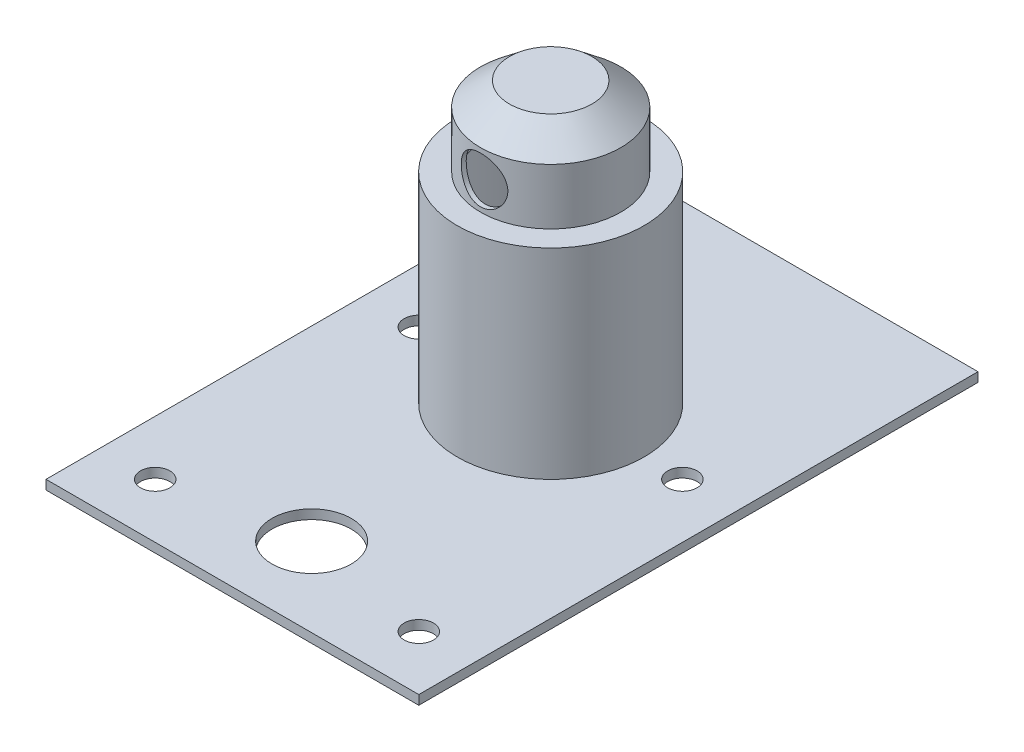
SolidWorks part; units mm, degrees
ref_plane "Front Plane" through (0, 0, 0) normal (0, 0, 1) x (1, 0, 0)
ref_plane "Top Plane" through (0, 0, 0) normal (0, 1, 0) x (1, 0, 0)
ref_plane "Right Plane" through (0, 0, 0) normal (1, 0, 0) x (0, 0, -1)
sketch "Sketch1" plane through (0, 0, 0) normal (0, 1, 0) x (1, 0, 0)
  line L0 (-35.5915, 84.198) -> (44.4085, 4.198) construction
  line L1 (-35.5915, 84.198) -> (44.4085, 84.198) construction
  line L2 (-35.5915, 84.198) -> (-35.5915, 4.198)
  line L3 (-35.5915, 4.198) -> (44.4085, 4.198)
  line L4 (44.4085, 84.198) -> (44.4085, 4.198)
  line L5 (-35.5915, 4.198) -> (44.4085, 84.198) construction
  line L6 (4.4085, 44.198) -> (106.3368, 44.198) construction
  line L7 (-35.5915, 84.198) -> (-35.5915, 124.198)
  line L8 (-35.5915, 124.198) -> (44.4085, 124.198)
  line L9 (44.4085, 124.198) -> (44.4085, 84.198)
  circle A0 centre (-23.8758, 72.4822) radius 3.15
  circle A4 centre (4.4085, 21.198) radius 8.5
  circle A8 centre (32.6928, 72.4822) radius 3.15
  circle A9 centre (-23.8758, 15.9137) radius 3.15
  circle A10 centre (32.6928, 15.9137) radius 3.15
  point P9 (4.4085, 44.198)
  point P15 (4.4085, 44.198)
  dimension "D1" = 6.3
  dimension "D4" = 23
  dimension "D5" = 17
  dimension "D2" = 40
  dimension "D6" = 80
  dimension "D3" = 120
extrude "Boss-Extrude1" add sketch "Sketch1" along normal blind 2
ref_plane "Plane1" through (0, 0, -72.5) normal (0, 0, 1) x (1, 0, 0)
sketch "Sketch2" plane through (0, 0, -72.5) normal (0, 0, 1) x (1, 0, 0)
  line L0 (4.4085, 20.1295) -> (4.4085, -8.3066) construction
  line L1 (44.4085, 2) -> (44.4085, 0) construction
  line L2 (-35.5915, 2) -> (-35.5915, 0) construction
  line L5 (4.4085, 62) -> (13.2501, 62)
  line L13 (19.4538, 57) -> (19.4538, 45)
  line L14 (19.4538, 45) -> (24.4538, 45)
  line L17 (24.4538, 45) -> (24.4538, 2)
  line L18 (-35.5915, 2) -> (44.4085, 2) construction
  line L19 (19.4538, 57) -> (13.2501, 62)
  line L20 (4.4085, 61) -> (12.8973, 61)
  line L21 (18.4538, 56.5216) -> (12.8973, 61)
  line L22 (18.4538, 56.5216) -> (18.4538, 44)
  line L23 (18.4538, 44) -> (23.4538, 44)
  line L24 (23.4538, 44) -> (23.4538, 2)
  line L25 (4.4085, 62) -> (4.4085, 61)
  line L26 (23.4538, 2) -> (24.4538, 2)
  dimension "D1" = 5
  dimension "D2" = 12
  dimension "D3" = 60
  dimension "D4" = 5
  dimension "D5" = 1
revolve "Revolve1" add sketch "Sketch2" angle 360 about L0
sketch "Sketch3" plane through (0, 0, -72.5) normal (0, 0, 1) x (1, 0, 0)
  line L0 (-18.8042, 51) -> (29.8352, 51) construction
  line L1 (-10.6368, 57) -> (19.4538, 57) construction
  line L2 (24.4538, 45) -> (-15.6368, 45) construction
  line L3 (4.4085, 62.4607) -> (4.4085, 37.8381) construction
  line L4 (19.4538, 57) -> (19.4538, 45) construction
  line L5 (-10.6368, 57) -> (-10.6368, 45) construction
  circle A0 centre (4.4085, 51) radius 5
  point P14 (0, 0)
  dimension "D1" = 10
extrude "Cut-Extrude1" cut sketch "Sketch3" against normal through all both and the other way through all
sketch "Sketch4" plane through (0, 2, 0) normal (0, 1, 0) x (1, 0, 0)
  circle A2 centre (4.4085, 72.5) radius 19.0453
  circle A3 centre (4.4085, 72.5) radius 19.0453
  dimension "D1" = 1
extrude "Cut-Extrude2" cut sketch "Sketch4" against normal through all
